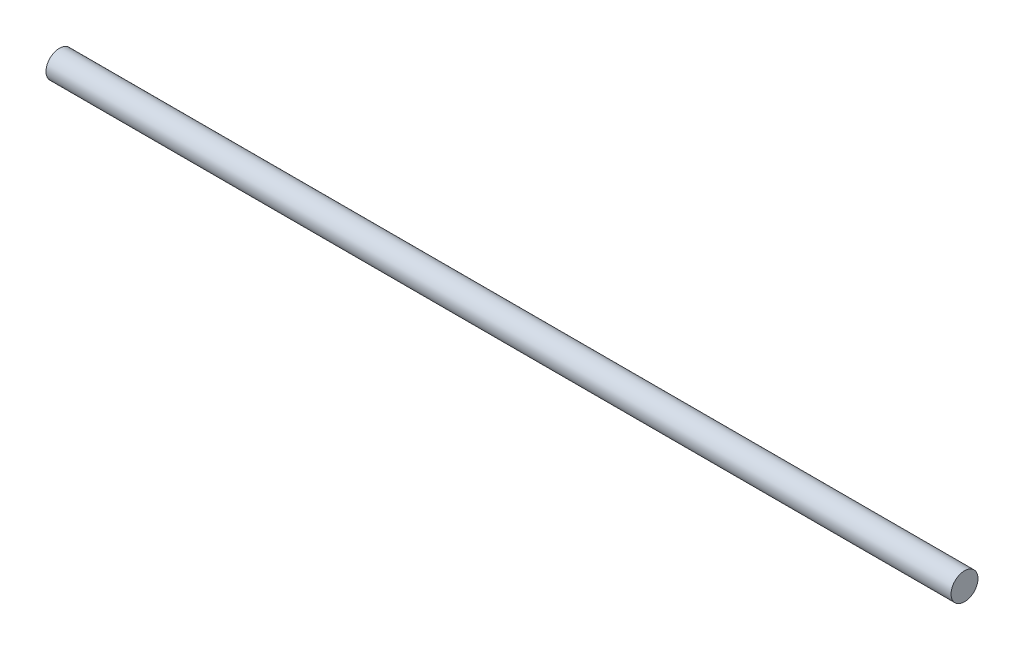
SolidWorks part; units mm, degrees
material "1060 Alloy"
ref_plane "Front Plane" through (0, 0, 0) normal (0, 0, 1) x (1, 0, 0)
ref_plane "Top Plane" through (0, 0, 0) normal (0, 1, 0) x (1, 0, 0)
ref_plane "Right Plane" through (0, 0, 0) normal (1, 0, 0) x (0, 0, -1)
sketch "Sketch1" plane through (0, 0, 0) normal (1, 0, 0) x (0, 0, -1)
  circle A0 centre (0, 0) radius 3.2
extrude "Boss-Extrude1" add sketch "Sketch1" along normal blind 215
